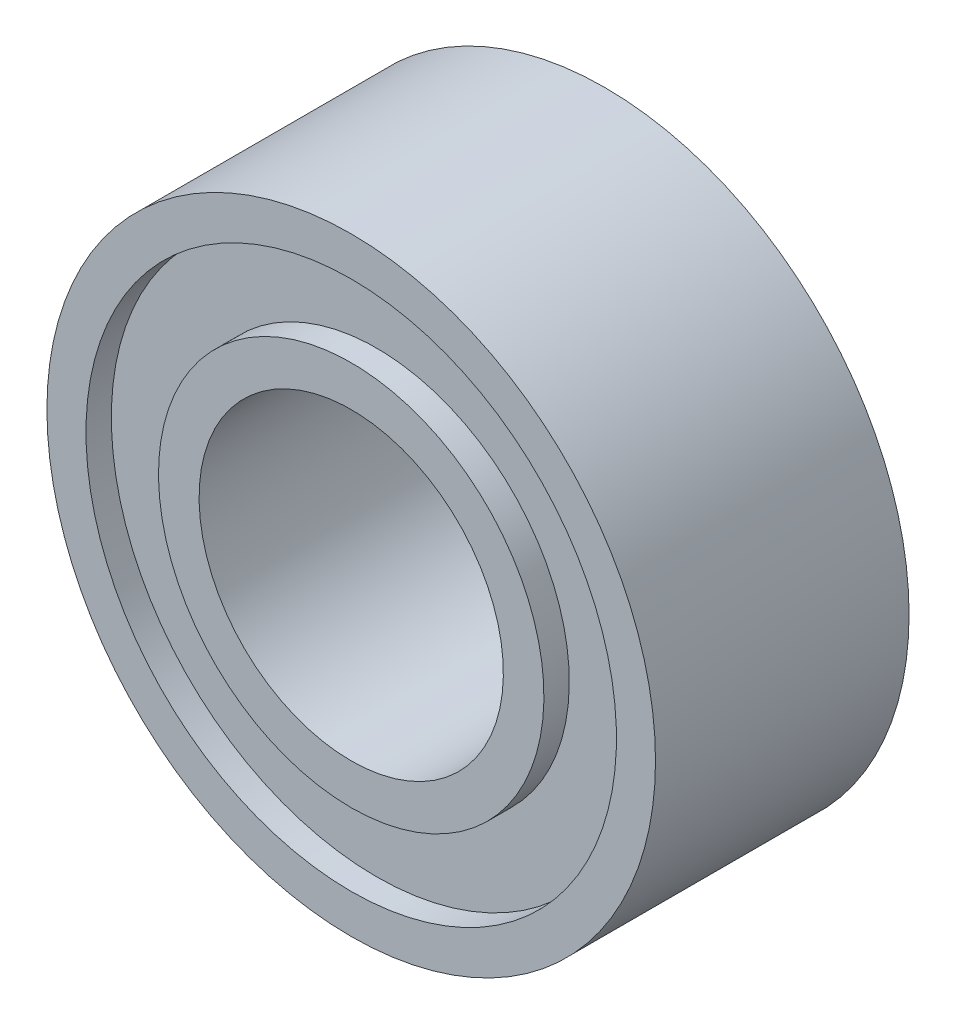
SolidWorks part; units mm, degrees
ref_plane "Front Plane" through (0, 0, 0) normal (0, 0, 1) x (1, 0, 0)
ref_plane "Top Plane" through (0, 0, 0) normal (0, 1, 0) x (1, 0, 0)
ref_plane "Right Plane" through (0, 0, 0) normal (1, 0, 0) x (0, 0, -1)
sketch "Sketch1" plane through (0, 0, 0) normal (1, 0, 0) x (0, 0, -1)
  line L0 (-1.25, 0) -> (1.25, 0) construction
  line L1 (-1.25, 3) -> (-1.25, 0) construction
  line L2 (-1.25, 3) -> (1.25, 3)
  line L3 (-1.25, 3) -> (-1.25, 2.615)
  line L4 (-1.25, 2.615) -> (-1, 2.615)
  line L5 (1.25, 3) -> (1.25, 2.615)
  line L6 (-1.25, 1.9) -> (-1, 1.9)
  line L7 (-1.25, 1.9) -> (-1.25, 1.5)
  line L8 (-1.25, 1.5) -> (1.25, 1.5)
  line L9 (1.25, 1.9) -> (1.25, 1.5)
  line L10 (1.25, 3) -> (1.25, 0) construction
  line L11 (-1, 2.615) -> (-1, 1.9)
  line L12 (0, 3) -> (0, 0) construction
  line L13 (1, 2.615) -> (1, 1.9)
  line L14 (1, 2.615) -> (1.25, 2.615)
  line L15 (1, 1.9) -> (1.25, 1.9)
  point P3 (0, 0)
  point P14 (0, 0)
  point P17 (-0.7611, 2.615)
  point P18 (-0.806, 1.9)
  dimension "D1" = 3
  dimension "D2" = 6
  dimension "D3" = 3.8
  dimension "D4" = 2.5
  dimension "D6" = 5.23
  dimension "D7" = 1
revolve "Revolve1" add sketch "Sketch1" angle 360 about L0
fillet "Fillet1" [suppressed] radius 0.15
fillet "Fillet2" [suppressed] radius 0.15
